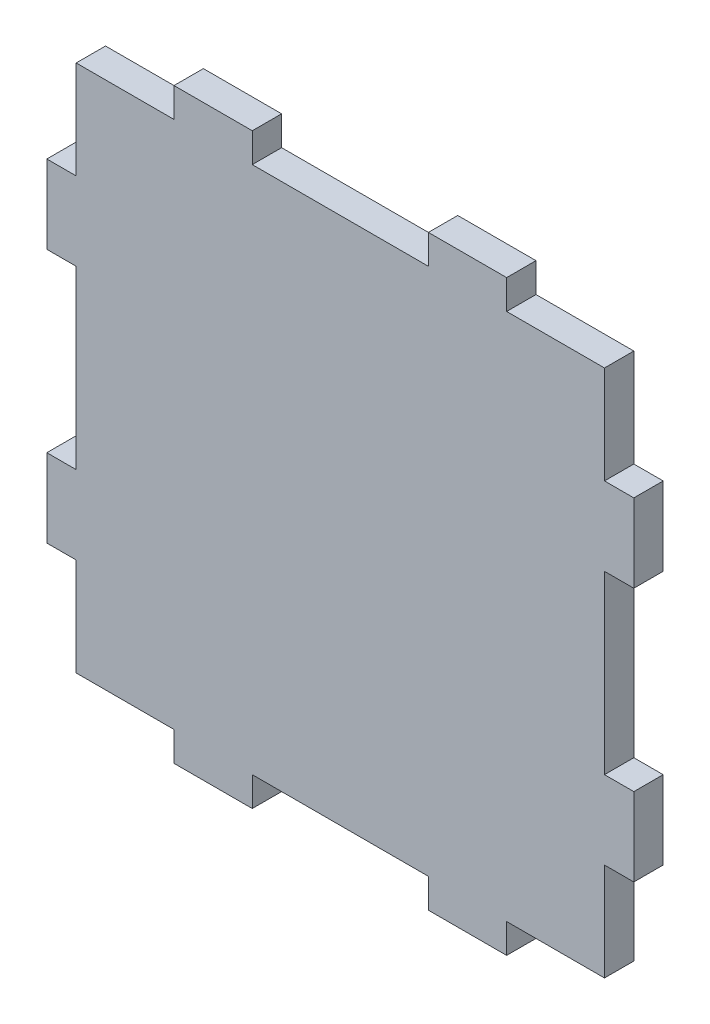
SolidWorks part; units mm, degrees
ref_plane "Front Plane" through (0, 0, 0) normal (0, 0, 1) x (1, 0, 0)
ref_plane "Top Plane" through (0, 0, 0) normal (0, 1, 0) x (1, 0, 0)
ref_plane "Right Plane" through (0, 0, 0) normal (1, 0, 0) x (0, 0, -1)
sketch "Sketch1" plane through (0, 0, 0) normal (0, 0, 1) x (1, 0, 0)
  line L0 (119.5585, 186.5704) -> (144.9585, 186.5704)
  line L1 (37.0085, 186.5704) -> (62.4085, 186.5704)
  line L2 (-4.2665, 145.2954) -> (-4.2665, 119.8954)
  line L3 (37.0085, -3.9296) -> (62.4085, -3.9296)
  line L4 (186.2335, 145.2954) -> (186.2335, 119.8954)
  line L7 (5.2585, 177.0454) -> (37.0085, 177.0454)
  line L8 (37.0085, 186.5704) -> (37.0085, 177.0454)
  line L11 (176.7085, 177.0454) -> (144.9585, 177.0454)
  line L12 (144.9585, 186.5704) -> (144.9585, 177.0454)
  line L14 (62.4085, 186.5704) -> (62.4085, 177.0454)
  line L15 (62.4085, 177.0454) -> (119.5585, 177.0454)
  line L16 (119.5585, 186.5704) -> (119.5585, 177.0454)
  line L17 (-4.2665, 62.7454) -> (-4.2665, 37.3454)
  line L20 (-4.2665, 145.2954) -> (5.2585, 145.2954)
  line L21 (5.2585, 177.0454) -> (5.2585, 145.2954)
  line L24 (186.2335, 145.2954) -> (176.7085, 145.2954)
  line L25 (176.7085, 177.0454) -> (176.7085, 145.2954)
  line L28 (-4.2665, 37.3454) -> (5.2585, 37.3454)
  line L29 (5.2585, 5.5954) -> (5.2585, 37.3454)
  line L32 (186.2335, 37.3454) -> (176.7085, 37.3454)
  line L33 (176.7085, 5.5954) -> (176.7085, 37.3454)
  line L34 (-4.2665, 119.8954) -> (5.2585, 119.8954)
  line L36 (-4.2665, 62.7454) -> (5.2585, 62.7454)
  line L37 (5.2585, 119.8954) -> (5.2585, 62.7454)
  line L38 (186.2335, 62.7454) -> (186.2335, 37.3454)
  line L39 (186.2335, 119.8954) -> (176.7085, 119.8954)
  line L41 (186.2335, 62.7454) -> (176.7085, 62.7454)
  line L42 (176.7085, 119.8954) -> (176.7085, 62.7454)
  line L43 (119.5585, -3.9296) -> (144.9585, -3.9296)
  line L44 (5.2585, 5.5954) -> (37.0085, 5.5954)
  line L47 (37.0085, 5.5954) -> (37.0085, -3.9296)
  line L50 (176.7085, 5.5954) -> (144.9585, 5.5954)
  line L51 (144.9585, -3.9296) -> (144.9585, 5.5954)
  line L52 (62.4085, 5.5954) -> (119.5585, 5.5954)
  line L53 (62.4085, 5.5954) -> (62.4085, -3.9296)
  line L55 (119.5585, 5.5954) -> (119.5585, -3.9296)
  point P12 (37.0085, 181.8079)
  point P39 (37.0085, 0.8329)
  dimension "D1" = 190.5
  dimension "D2" = 190.5
  dimension "D3" = 9.525
  dimension "D4" = 41.275
  dimension "D5" = 9.525
  dimension "D6" = 41.275
  dimension "D7" = 25.4
  dimension "D8" = 25.4
  dimension "D9" = 31.75
  dimension "D10" = 9.525
  dimension "D11" = 9.525
  dimension "D12" = 31.75
  dimension "D13" = 41.275
  dimension "D14" = 41.275
  dimension "D15" = 9.525
  dimension "D16" = 9.525
  dimension "D17" = 25.4
  dimension "D18" = 25.4
  dimension "D19" = 25.4
  dimension "D20" = 25.4
  dimension "D21" = 31.75
  dimension "D22" = 9.525
  dimension "D23" = 25.4
  dimension "D24" = 25.4
  dimension "D25" = 31.75
  dimension "D26" = 9.525
  dimension "D27" = 9.525
extrude "Boss-Extrude1" add sketch "Sketch1" along normal blind 9.525
sketch "Sketch2" plane through (0, 0, 9.525) normal (0, 0, 1) x (1, 0, 0)
  line L1 (44.5102, 89.6675) -> (60.5585, 89.6675)
  line L2 (44.5102, 89.6675) -> (44.5102, 61.5829)
  line L3 (44.5102, 61.5829) -> (60.5585, 61.5829)
  line L4 (60.5585, 89.6675) -> (60.5585, 61.5829)
